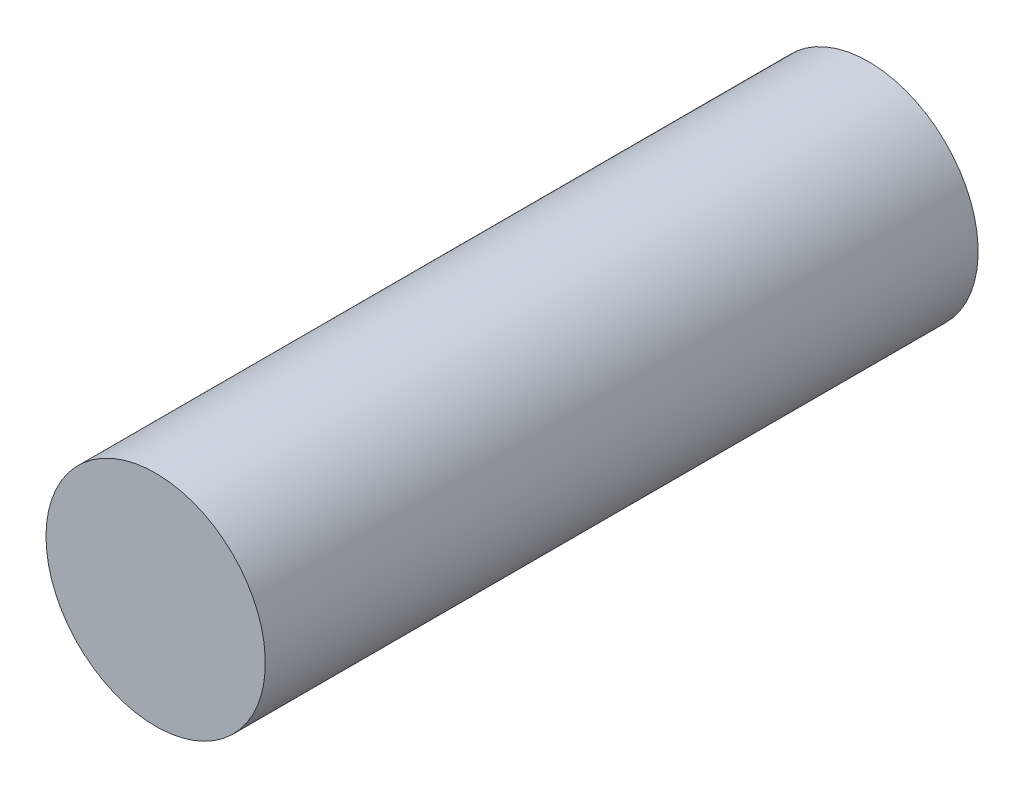
SolidWorks part; units mm, degrees
ref_plane "Спереди" through (0, 0, 0) normal (0, 0, 1) x (1, 0, 0)
ref_plane "Сверху" through (0, 0, 0) normal (0, 1, 0) x (1, 0, 0)
ref_plane "Справа" through (0, 0, 0) normal (1, 0, 0) x (0, 0, -1)
sketch "Эскиз1" plane through (0, 0, 0) normal (0, 0, 1) x (1, 0, 0)
  circle A0 centre (0, 0) radius 4
extrude "Planet_pin" add sketch "Эскиз1" along normal blind 26 from offset 32
